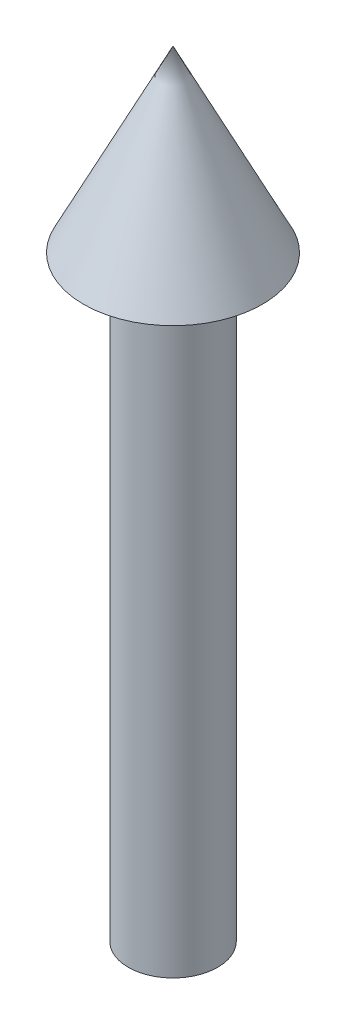
SolidWorks part; units mm, degrees
ref_plane "Front Plane" through (0, 0, 0) normal (0, 0, 1) x (1, 0, 0)
ref_plane "Top Plane" through (0, 0, 0) normal (0, 1, 0) x (1, 0, 0)
ref_plane "Right Plane" through (0, 0, 0) normal (1, 0, 0) x (0, 0, -1)
sketch "Sketch1" plane through (0, 0, 0) normal (0, 1, 0) x (1, 0, 0)
  circle A0 centre (0, 0) radius 1.5
  dimension "D1" = 3
extrude "Boss-Extrude1" add sketch "Sketch1" along normal blind 20
sketch "Sketch3" plane through (0, 0, 0) normal (1, 0, 0) x (0, 0, -1)
  line L0 (0, 20) -> (-3, 20)
  line L1 (1.5, 20) -> (-1.5, 20) construction
  line L2 (-3, 20) -> (0, 26)
  line L3 (0, 26) -> (0, 20)
  dimension "D1" = 3
  dimension "D2" = 6
revolve "Revolve1" add sketch "Sketch3" angle 360 about L3
